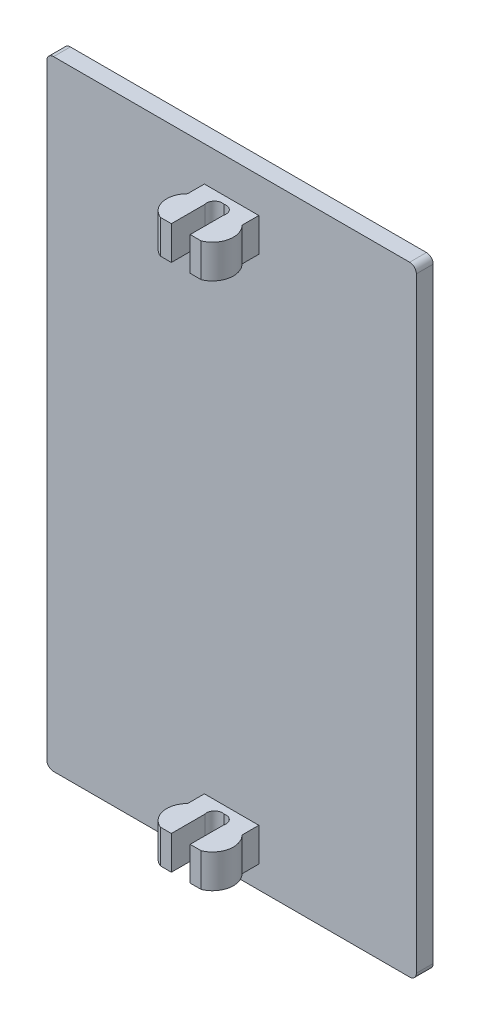
SolidWorks part; units mm, degrees
ref_plane "Front Plane" through (0, 0, 0) normal (0, 0, 1) x (1, 0, 0)
ref_plane "Top Plane" through (0, 0, 0) normal (0, 1, 0) x (1, 0, 0)
ref_plane "Right Plane" through (0, 0, 0) normal (1, 0, 0) x (0, 0, -1)
sketch "Sketch1" plane through (0, 0, 0) normal (0, 0, 1) x (1, 0, 0)
  line L1 (-27.5, 46.0719) -> (27.5, 46.0719)
  line L2 (-27.5, 46.0719) -> (-27.5, -46.0719)
  line L3 (-27.5, -46.0719) -> (27.5, -46.0719)
  line L4 (27.5, 46.0719) -> (27.5, -46.0719)
  point P4 (0, 46.0719)
  point P6 (-27.5, 0)
  dimension "D1" = 92.1439
  dimension "D2" = 55
extrude "Boss-Extrude1" add sketch "Sketch1" along normal blind 2.5
sketch "Sketch4" plane through (0, 0, 0) normal (1, 0, 0) x (0, 0, -1)
  line L0 (0, -46.0719) -> (0, 46.0719) construction
  line L1 (-2.5, 46.0719) -> (0, 46.0719) construction
  point P0 (0, 38.3719)
  point P1 (0, -40.2281)
  point P4 (0, 0)
  point P5 (0, 0)
  dimension "D1" = 78.6
  dimension "D2" = 7.7
ref_plane "Plane1" through (0, 38.3719, 0) normal (0, 1, 0) x (1, 0, 0)
ref_plane "Plane2" through (0, -40.2281, 0) normal (0, -1, 0) x (-1, 0, 0)
sketch "Sketch6" plane through (0, 38.3719, 0) normal (0, 1, 0) x (1, 0, 0)
  line L0 (0, 0) -> (0, -13.8724) construction
  line L1 (-4.053, -5) -> (-4.053, -2.5)
  line L2 (-3.0361, -10.0668) -> (-1.4, -10.0668)
  line L3 (-1.4, -10.0668) -> (-1.4, -5.0668)
  line L4 (-4.053, -2.5) -> (4.053, -2.5)
  line L5 (1.4, -10.0668) -> (1.4, -5.0668)
  line L6 (3.0361, -10.0668) -> (1.4, -10.0668)
  line L7 (4.053, -5) -> (4.053, -2.5)
  line L8 (27.5, -2.5) -> (-27.5, -2.5) construction
  arc A0 (-1.4, -5.0668) -> (0, -3.6424) centre (-0.289, -4.7586) cw
  arc A1 (-3.0361, -10.0668) -> (-4.053, -5) centre (-1.8537, -7.1941) cw
  arc A2 (3.0361, -10.0668) -> (4.053, -5) centre (1.8537, -7.1941) ccw
  arc A3 (1.4, -5.0668) -> (0, -3.6424) centre (0.289, -4.7586) ccw
  point P14 (0, -2.5)
  point P18 (0, -2.5)
  point P21 (0, 0)
  dimension "D5" = 3.1066
  dimension "D8" = 1.153
  dimension "D1" = 5.0668
  dimension "D2" = 1.4
  dimension "D3" = 2.653
  dimension "D4" = 1.6361
  dimension "D6" = 5
  dimension "D7" = 1.4244
  dimension "D9" = 2.5
extrude "Boss-Extrude2" add sketch "Sketch6" along normal mid plane 5
sketch "Sketch7" plane through (0, -40.2281, 0) normal (0, -1, 0) x (-1, 0, 0)
  line L0 (0, 0) -> (0, -13.8724) construction
  line L1 (-4.053, -5) -> (-4.053, -2.5)
  line L2 (-3.0361, -10.0668) -> (-1.4, -10.0668)
  line L3 (-1.4, -10.0668) -> (-1.4, -5.0668)
  line L4 (-4.053, -2.5) -> (4.053, -2.5)
  line L5 (1.4, -10.0668) -> (1.4, -5.0668)
  line L6 (3.0361, -10.0668) -> (1.4, -10.0668)
  line L7 (4.053, -5) -> (4.053, -2.5)
  line L8 (27.5, -2.5) -> (-27.5, -2.5) construction
  arc A0 (-1.4, -5.0668) -> (0, -3.6424) centre (-0.289, -4.7586) cw
  arc A1 (-3.0361, -10.0668) -> (-4.053, -5) centre (-1.8537, -7.1941) cw
  arc A2 (3.0361, -10.0668) -> (4.053, -5) centre (1.8537, -7.1941) ccw
  arc A3 (1.4, -5.0668) -> (0, -3.6424) centre (0.289, -4.7586) ccw
  point P14 (0, -2.5)
  point P18 (0, -2.5)
  point P21 (0, 0)
  dimension "D5" = 3.1066
  dimension "D8" = 1.153
  dimension "D1" = 5.0668
  dimension "D2" = 1.4
  dimension "D3" = 2.653
  dimension "D4" = 1.6361
  dimension "D6" = 5
  dimension "D7" = 1.4244
  dimension "D9" = 2.5
extrude "Boss-Extrude3" add sketch "Sketch7" along normal mid plane 5
fillet "Fillet1" radius 1 4 edges at (27.5, 46.0719, 1.25) (-27.5, 46.0719, 1.25) (27.5, -46.0719, 1.25) (-27.5, -46.0719, 1.25)
